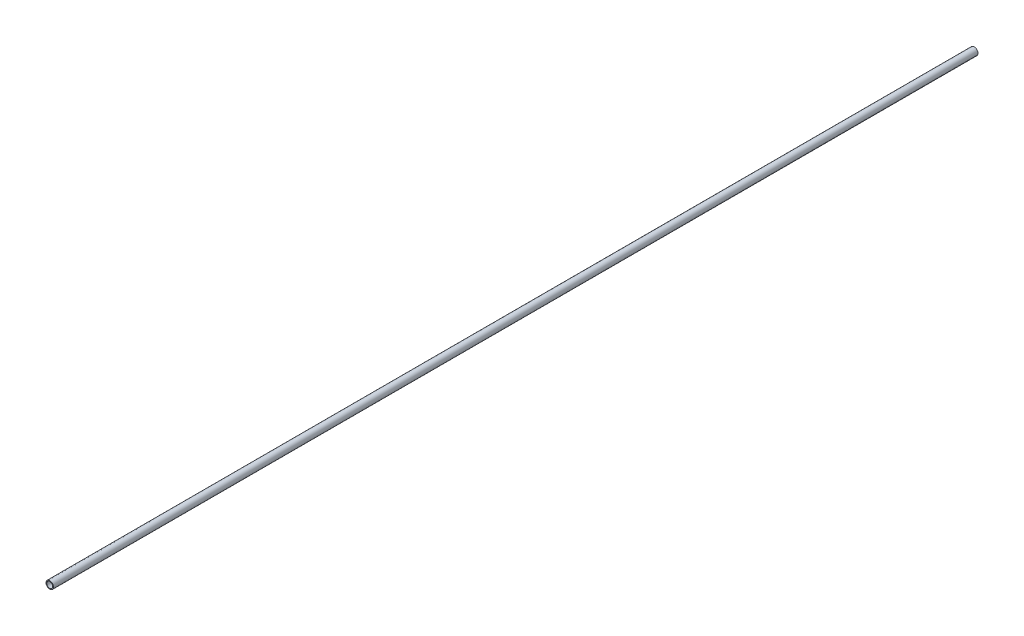
SolidWorks part; units mm, degrees
material "Thornel Mat VMA"
ref_plane "前视基准面" through (0, 0, 0) normal (0, 0, 1) x (1, 0, 0)
ref_plane "上视基准面" through (0, 0, 0) normal (0, 1, 0) x (1, 0, 0)
ref_plane "右视基准面" through (0, 0, 0) normal (1, 0, 0) x (0, 0, -1)
other "Configuration Table"
sketch "草图1" plane through (0, 0, 0) normal (0, 0, 1) x (1, 0, 0)
  circle A0 centre (0, 0) radius 5
  circle A1 centre (0, 0) radius 4
  dimension "D1" = 10
  dimension "D2" = 8
extrude "凸台-拉伸1" add sketch "草图1" along normal blind 1233
